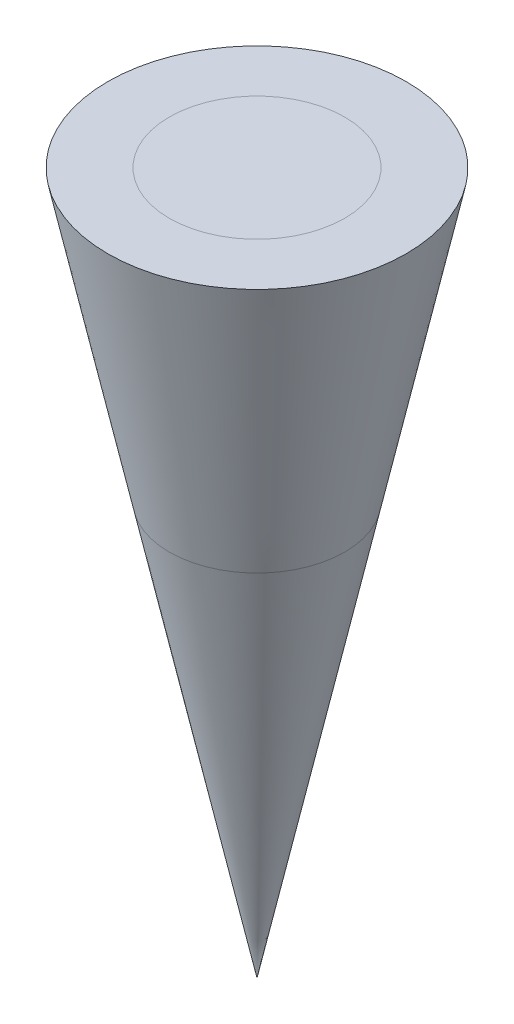
SolidWorks part; units mm, degrees
ref_plane "Front Plane" through (0, 0, 0) normal (0, 0, 1) x (1, 0, 0)
ref_plane "Top Plane" through (0, 0, 0) normal (0, 1, 0) x (1, 0, 0)
ref_plane "Right Plane" through (0, 0, 0) normal (1, 0, 0) x (0, 0, -1)
sketch "Sketch1" plane through (0, 0, 0) normal (0, 1, 0) x (1, 0, 0)
  line L1 (5.2107, -2.4864) -> (4.7586, 3.2693)
  line L2 (4.7586, 3.2693) -> (-0.452, 5.7558)
  line L3 (-0.452, 5.7558) -> (-5.2107, 2.4864)
  line L4 (-5.2107, 2.4864) -> (-4.7586, -3.2693)
  line L5 (-4.7586, -3.2693) -> (0.452, -5.7558)
  line L6 (0.452, -5.7558) -> (5.2107, -2.4864)
  circle A0 centre (0, 0) radius 5 construction
  point P1 (-2.8313, 4.1211)
  dimension "D1" = 10
extrude "Boss-Extrude1" add sketch "Sketch1" along normal blind 10
sketch "Sketch2" plane through (0, 10, 0) normal (0, 1, 0) x (1, 0, 0)
  circle A0 centre (0, 0) radius 1.25
  dimension "D1" = 2.5
split "Split1" trim tools "Sketch2" bodies to split 101 resulting bodies 102 103
sketch "Sketch4" plane through (0, 0, 0) normal (0, 0, 1) x (1, 0, 0)
  line L0 (0, 0) -> (6.3767, 30)
  line L1 (6.3767, 30) -> (6.3767, -2.0368)
  line L2 (6.3767, -2.0368) -> (0, -2.0368)
  line L3 (0, -2.0368) -> (0, 0)
  line L4 (0, 0) -> (0, 5.8669) construction
  line L5 (0.452, 0) -> (5.2107, 0) construction
  dimension "D1" = 12
  dimension "D2" = 30
revolve "Cut-Revolve1" cut sketch "Sketch4" angle 360 about L4
